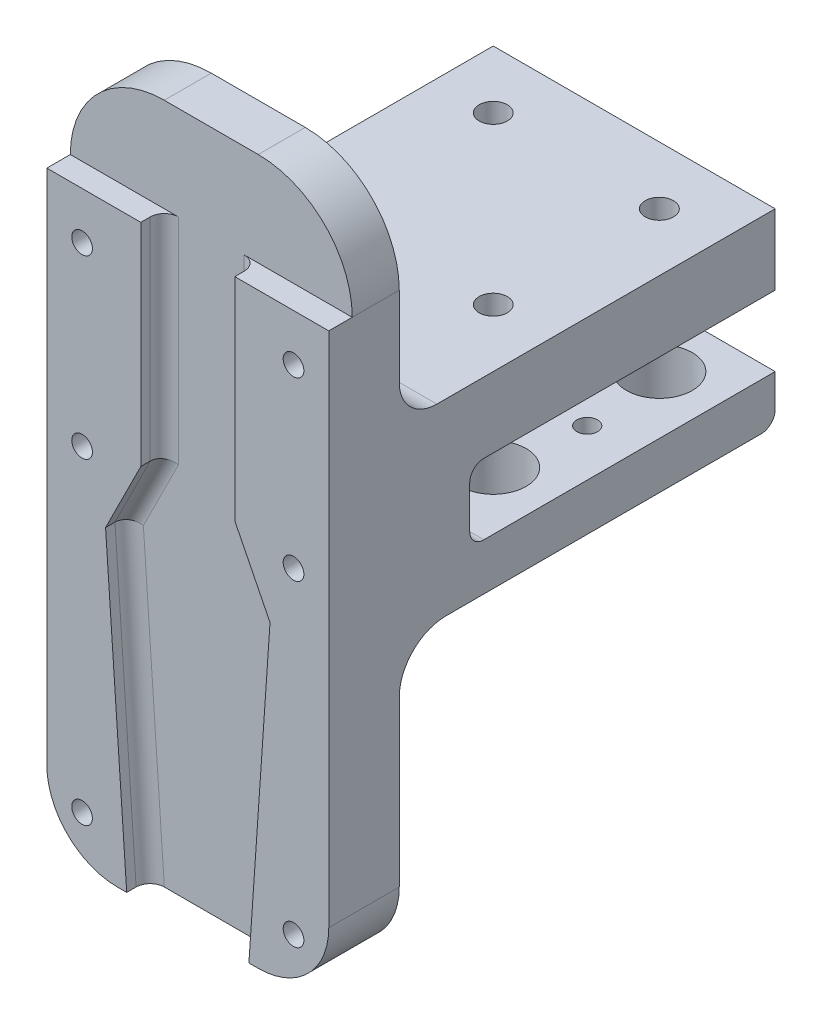
SolidWorks part; units mm, degrees
material "ABS"
ref_plane "Front Plane" through (0, 0, 0) normal (0, 0, 1) x (1, 0, 0)
ref_plane "Top Plane" through (0, 0, 0) normal (0, 1, 0) x (1, 0, 0)
ref_plane "Right Plane" through (0, 0, 0) normal (1, 0, 0) x (0, 0, -1)
sketch "草图8" plane through (0, 0, 0) normal (0, 1, 0) x (1, 0, 0)
  line L0 (-30, -30) -> (-17.6777, -17.6777)
  line L1 (-30, 30) -> (30, 30)
  line L2 (-30, 30) -> (-30, -30)
  line L3 (-30, -30) -> (30, -30)
  line L4 (30, 30) -> (30, -30)
  line L5 (-30, 30) -> (30, -30) construction
  line L6 (-30, -30) -> (30, 30) construction
  line L7 (-30, 30) -> (-17.6777, 17.6777)
  line L8 (17.6777, 17.6777) -> (30, 30)
  line L9 (17.6777, -17.6777) -> (30, -30)
  circle A0 centre (0, 0) radius 25
  circle A1 centre (17.6777, 17.6777) radius 3
  circle A2 centre (-17.6777, 17.6777) radius 3
  circle A3 centre (-17.6777, -17.6777) radius 3
  circle A4 centre (17.6777, -17.6777) radius 3
  point P0 (0, 0)
extrude "凸台-拉伸7" add sketch "草图8" along normal blind 15 contours A4 A0 A3 L0 L3 L9 | A4 L9 L4 L8 A1 A0 | A2 A0 A1 L8 L1 L7 | A3 A0 A2 L7 L2 L0 | A4 A0 A1 A2 A3
sketch "草图10" plane through (0, 0, 30) normal (0, 0, 1) x (1, 0, 0)
  line L1 (-30, 15) -> (30, 15)
  line L2 (-30, 15) -> (-30, 0)
  line L3 (-30, 0) -> (30, 0)
  line L4 (30, 15) -> (30, 0)
extrude "凸台-拉伸8" add sketch "草图10" along normal blind 30
sketch "草图11" plane through (0, 0, 0) normal (0, -1, 0) x (1, 0, 0)
  line L0 (-30, -30) -> (-30, 60) construction
  line L1 (30, 60) -> (-30, 60)
  line L2 (30, 60) -> (30, 50)
  line L3 (30, 50) -> (-30, 50)
  line L4 (-30, 60) -> (-30, 50)
extrude "凸台-拉伸9" add sketch "草图11" against normal blind 60
sketch "草图12" plane through (0, 0, 0) normal (0, -1, 0) x (-1, 0, 0)
  line L0 (-30, 30) -> (-30, -60) construction
  line L1 (30, -60) -> (-30, -60)
  line L2 (30, -60) -> (30, -50)
  line L3 (30, -50) -> (-30, -50)
  line L4 (-30, -60) -> (-30, -50)
extrude "凸台-拉伸10" add sketch "草图12" along normal blind 90
sketch "草图13" plane through (0, 0, 50) normal (0, 0, -1) x (-1, 0, 0)
  line L0 (30, -90) -> (30, 0) construction
  line L1 (-30, 0) -> (30, 0)
  line L2 (-30, 0) -> (-30, -15)
  line L3 (-30, -15) -> (30, -15)
  line L4 (30, 0) -> (30, -15)
  line L6 (-30, -15) -> (30, -15)
  line L7 (-30, -15) -> (-30, -25)
  line L8 (-30, -25) -> (30, -25)
  line L9 (30, -15) -> (30, -25)
  line M10 (-30, 0) -> (-30, -90)
  line M12 (30, -90) -> (30, 0)
extrude "凸台-拉伸11" add sketch "草图13" along normal up to surface (80 mm away) contours L8 L3 M10 M12 up to face at (0, 7.5, -30)
sketch "草图14" plane through (0, -25, 0) normal (0, -1, 0) x (1, 0, 0)
  line L0 (-30, -30) -> (-30, 50) construction
  line L1 (30, -30) -> (-30, -30)
  line L2 (30, -30) -> (30, 30)
  line L3 (30, 30) -> (-30, 30)
  line L4 (-30, -30) -> (-30, 30)
  line L5 (-30, 30) -> (-17.6777, 17.6777)
  line L6 (30, 30) -> (17.6777, 17.6777)
  line L7 (-17.6777, -17.6777) -> (-30, -30)
  line L8 (17.6777, -17.6777) -> (30, -30)
  circle A0 centre (0, 0) radius 25
  circle A1 centre (17.6777, 17.6777) radius 7
  circle A2 centre (17.6777, -17.6777) radius 7
  circle A3 centre (-17.6777, -17.6777) radius 7
  circle A4 centre (-17.6777, 17.6777) radius 7
extrude "切除-拉伸1" cut sketch "草图14" against normal up to surface (10 mm away) contours A0 A4 | A0 A1 | A0 A2 | A0 A3 | L5 A4 A0 | A0 A4 L5 | L6 A1 A0 | A0 A1 L6 | L8 A2 A0 | A0 A2 L8 | L7 A3 A0 | A0 A3 L7
sketch "草图15" plane through (0, 0, 0) normal (0, -1, 0) x (1, 0, 0)
  circle A0 centre (-17.6777, 17.6777) radius 6
  circle A1 centre (-17.6777, -17.6777) radius 6
  circle A2 centre (17.6777, -17.6777) radius 6
  circle A3 centre (17.6777, 17.6777) radius 6
extrude "切除-拉伸2" cut sketch "草图15" against normal blind 7
sketch "草图16" plane through (0, -25, 0) normal (0, -1, 0) x (-1, 0, 0)
  line L0 (30, 30) -> (30, -50) construction
  line L1 (-30, 30) -> (30, 30)
  line L2 (-30, 30) -> (-30, -30)
  line L3 (-30, -30) -> (30, -30)
  line L4 (30, 30) -> (30, -30)
  circle A0 centre (0, 0) radius 20
  circle A1 centre (-20, 0) radius 2.2
  circle A2 centre (0, 20) radius 2.2
  circle A3 centre (20, 0) radius 2.2
  circle A4 centre (0, -20) radius 2.2
extrude "切除-拉伸3" cut sketch "草图16" against normal up to surface (10 mm away) contours A0 A1 | A0 A1 | A0 A4 | A0 A4 | A0 A3 | A0 A3 | A0 A2 | A0 A2
sketch "草图17" plane through (0, -25, 0) normal (0, -1, 0) x (1, 0, 0)
  circle A0 centre (20, 0) radius 3.75
  circle A1 centre (0, -20) radius 3.75
  circle A2 centre (0, 20) radius 3.75
  circle A3 centre (-20, 0) radius 3.75
extrude "切除-拉伸4" cut sketch "草图17" against normal blind 4.5
sketch "草图18" plane through (0, 0, 50) normal (0, 0, -1) x (-1, 0, 0)
  line L0 (30, 0) -> (-30, 0) construction
  line L1 (-30, -15) -> (30, -15)
  line L2 (-30, -15) -> (-30, 0)
  line L3 (-30, 0) -> (30, 0)
  line L4 (30, -15) -> (30, 0)
extrude "凸台-拉伸12" add sketch "草图18" along normal blind 15
fillet "圆角1" radius 3 1 edges at (0, -25, -30)
fillet "圆角2" radius 10 1 edges at (0, -25, 50)
fillet "圆角3" radius 3 2 edges at (0, -15, 35) (0, 0, 35)
fillet "圆角4" radius 8 1 edges at (0, 15, 50)
sketch "草图19" plane through (0, 0, 60) normal (0, 0, 1) x (1, 0, 0)
  line L0 (0, 40) -> (0, -85)
  line L1 (-30, 60) -> (30, 60)
  line L5 (30, -90) -> (30, 60) construction
  line L10 (-30, 60) -> (30, 60)
  line L11 (-30, 60) -> (-30, 40)
  line L12 (-30, 40) -> (30, 40)
  line L13 (30, 60) -> (30, 40)
  line L14 (17.5, -20) -> (10, -5)
  line L15 (-30, 40) -> (30, 40)
  line L16 (-30, 40) -> (-30, -85)
  line L17 (-30, -85) -> (30, -85)
  line L18 (30, 40) -> (30, -85)
  line L19 (0, -85) -> (13, -85)
  line L20 (0, -85) -> (0, -20)
  line L21 (0, -20) -> (13, -20)
  line L22 (13, -85) -> (13, -20)
  line L23 (0, -85) -> (-13, -85)
  line L24 (0, -85) -> (0, -20)
  line L25 (0, -20) -> (-13, -20)
  line L26 (-13, -85) -> (-13, -20)
  line L27 (0, -85) -> (17.5, -85)
  line L28 (0, -85) -> (0, -20)
  line L29 (0, -20) -> (17.5, -20)
  line L30 (17.5, -85) -> (17.5, -20)
  line L31 (0, -85) -> (-17.5, -85)
  line L32 (0, -85) -> (0, -20)
  line L33 (0, -20) -> (-17.5, -20)
  line L34 (-17.5, -85) -> (-17.5, -20)
  line L35 (30, 40) -> (10, 40)
  line L36 (30, 40) -> (30, -5)
  line L37 (30, -5) -> (10, -5)
  line L38 (10, 40) -> (10, -5)
  line L39 (-30, 40) -> (-10, 40)
  line L40 (-30, 40) -> (-30, -5)
  line L41 (-30, -5) -> (-10, -5)
  line L42 (-10, 40) -> (-10, -5)
  line L43 (-10, -5) -> (-17.5, -20)
  line L44 (-17.5, -20) -> (-13, -85)
  line L45 (17.5, -20) -> (13, -85)
  line M40 (-30, 60) -> (-30, -90)
  line M42 (30, -90) -> (30, 60)
extrude "凸台-拉伸13" add sketch "草图19" along normal blind 5 contours L37 L14 L30 L17 M42 | L15 L38 L37 L18 | L42 L12 L41 M40 | L43 L41 L16 L17 L34 | L44 L34 L17 | L30 L45 L17
sketch "草图20" plane through (0, 0, 60) normal (0, 0, 1) x (1, 0, 0)
  line L1 (-30, -90) -> (30, -90)
  line L2 (-30, -90) -> (-30, -85)
  line L3 (-30, -85) -> (30, -85)
  line L4 (30, -90) -> (30, -85)
extrude "切除-拉伸5" cut sketch "草图20" against normal through all
fillet "圆角5" radius 3 6 edges at (10, 17.5, 60) (13.75, -12.5, 60) (15.25, -52.5, 60) (-15.25, -52.5, 60) (-13.75, -12.5, 60) (-10, 17.5, 60)
fillet "圆角6" radius 15 2 edges at (30, -85, 57.5) (-30, -85, 57.5)
sketch "草图22" plane through (0, 0, 65) normal (0, 0, 1) x (1, 0, 0)
  line L0 (30, 40) -> (30, -85)
  line L1 (0, -85) -> (30, -85)
  line L2 (9.9928, -85) -> (-9.9928, -85) construction
  line L3 (30, -85) -> (-30, 40)
  line L4 (30, -85) -> (-30, -85)
  line L5 (30, -85) -> (30, 40)
  line L6 (30, 40) -> (-30, 40)
  line L7 (-30, -85) -> (-30, 40)
  line L9 (22.5, 30) -> (-22.5, 30)
  line L10 (22.5, 30) -> (22.5, -75)
  line L11 (22.5, -75) -> (-22.5, -75)
  line L12 (-22.5, 30) -> (-22.5, -75)
  line L13 (22.5, 30) -> (-22.5, -75) construction
  line L14 (22.5, -75) -> (-22.5, 30) construction
  circle A0 centre (-22.5, 30) radius 2.2
  circle A1 centre (22.5, 30) radius 2.2
  circle A2 centre (-22.5, -75) radius 2.2
  circle A3 centre (22.5, -75) radius 2.2
  point P8 (0, -22.5)
extrude "切除-拉伸6" cut sketch "草图22" against normal through all contours L12 A2 L11 | L11 A2 L12 | L11 A3 L10 | L10 A3 L11 | L9 A0 L12 | L12 A0 L9 | L9 A1 L10 | L10 A1 L9
sketch "草图23" plane through (0, 0, 35) normal (0, 0, -1) x (-1, 0, 0)
  line L0 (30, -7.5) -> (-30, -7.5)
  line L1 (30, -3) -> (-30, -3)
  line L2 (30, -3) -> (30, -12)
  line L3 (30, -12) -> (-30, -12)
  line L4 (-30, -3) -> (-30, -12)
  circle A0 centre (0, -7.5) radius 22.5
  circle A1 centre (22.5, -7.5) radius 2.2
  circle A2 centre (-22.5, -7.5) radius 2.2
extrude "切除-拉伸7" cut sketch "草图23" against normal through all contours A0 A1 L0 | L0 A1 A0 | A0 A1 L0 | L0 A1 A0 | L0 A2 A0 | A0 A2 L0 | L0 A2 A0 | A0 A2 L0
sketch "草图24" plane through (0, 0, 50) normal (0, 0, -1) x (-1, 0, 0)
  line L1 (26.7, 30) -> (24.6, 33.6373)
  line L2 (24.6, 33.6373) -> (20.4, 33.6373)
  line L3 (20.4, 33.6373) -> (18.3, 30)
  line L4 (18.3, 30) -> (20.4, 26.3627)
  line L5 (20.4, 26.3627) -> (24.6, 26.3627)
  line L6 (24.6, 26.3627) -> (26.7, 30)
  line L7 (-26.7, 30) -> (-24.6, 26.3627)
  line L8 (-24.6, 26.3627) -> (-20.4, 26.3627)
  line L9 (-20.4, 26.3627) -> (-18.3, 30)
  line L10 (-18.3, 30) -> (-20.4, 33.6373)
  line L11 (-20.4, 33.6373) -> (-24.6, 33.6373)
  line L12 (-24.6, 33.6373) -> (-26.7, 30)
  line L13 (18.3, -7.5) -> (20.4, -11.1373)
  line L14 (20.4, -11.1373) -> (24.6, -11.1373)
  line L15 (24.6, -11.1373) -> (26.7, -7.5)
  line L16 (26.7, -7.5) -> (24.6, -3.8627)
  line L17 (24.6, -3.8627) -> (20.4, -3.8627)
  line L18 (20.4, -3.8627) -> (18.3, -7.5)
  line L19 (-26.7, -7.5) -> (-24.6, -11.1373)
  line L20 (-24.6, -11.1373) -> (-20.4, -11.1373)
  line L21 (-20.4, -11.1373) -> (-18.3, -7.5)
  line L22 (-18.3, -7.5) -> (-20.4, -3.8627)
  line L23 (-20.4, -3.8627) -> (-24.6, -3.8627)
  line L24 (-24.6, -3.8627) -> (-26.7, -7.5)
  line L25 (18.3, -75) -> (20.4, -78.6373)
  line L26 (20.4, -78.6373) -> (24.6, -78.6373)
  line L27 (24.6, -78.6373) -> (26.7, -75)
  line L28 (26.7, -75) -> (24.6, -71.3627)
  line L29 (24.6, -71.3627) -> (20.4, -71.3627)
  line L30 (20.4, -71.3627) -> (18.3, -75)
  line L31 (-18.3, -75) -> (-20.4, -71.3627)
  line L32 (-20.4, -71.3627) -> (-24.6, -71.3627)
  line L33 (-24.6, -71.3627) -> (-26.7, -75)
  line L34 (-26.7, -75) -> (-24.6, -78.6373)
  line L35 (-24.6, -78.6373) -> (-20.4, -78.6373)
  line L36 (-20.4, -78.6373) -> (-18.3, -75)
  circle A0 centre (22.5, 30) radius 4.2 construction
  circle A1 centre (-22.5, 30) radius 4.2 construction
  circle A2 centre (22.5, -7.5) radius 4.2 construction
  circle A3 centre (-22.5, -7.5) radius 4.2 construction
  circle A4 centre (22.5, -75) radius 4.2 construction
  circle A5 centre (-22.5, -75) radius 4.2 construction
extrude "切除-拉伸8" cut sketch "草图24" against normal blind 4.5
sketch "草图25" plane through (0, 0, 35) normal (0, 0, -1) x (-1, 0, 0)
  line L1 (18.3, -7.5) -> (20.4, -11.1373)
  line L2 (20.4, -11.1373) -> (24.6, -11.1373)
  line L3 (24.6, -11.1373) -> (26.7, -7.5)
  line L4 (26.7, -7.5) -> (24.6, -3.8627)
  line L5 (24.6, -3.8627) -> (20.4, -3.8627)
  line L6 (20.4, -3.8627) -> (18.3, -7.5)
  line L7 (-18.3, -7.5) -> (-20.4, -3.8627)
  line L8 (-20.4, -3.8627) -> (-24.6, -3.8627)
  line L9 (-24.6, -3.8627) -> (-26.7, -7.5)
  line L10 (-26.7, -7.5) -> (-24.6, -11.1373)
  line L11 (-24.6, -11.1373) -> (-20.4, -11.1373)
  line L12 (-20.4, -11.1373) -> (-18.3, -7.5)
  circle A0 centre (22.5, -7.5) radius 4.2 construction
  circle A1 centre (-22.5, -7.5) radius 4.2 construction
extrude "切除-拉伸9" cut sketch "草图25" against normal up to surface (15 mm away) up to face at (22.5, 30, 50)
sketch "草图26" plane through (0, 0, 35) normal (0, 0, -1) x (-1, 0, 0)
  circle A0 centre (22.5, -7.5) radius 4.2
  circle A1 centre (-22.5, -7.5) radius 4.2
extrude "切除-拉伸10" cut sketch "草图26" against normal up to surface (15 mm away) up to face at (-22.5, -75, 50)
fillet "圆角7" radius 20 2 edges at (-30, 60, 55) (30, 60, 55)
sketch "草图27" plane through (0, 15, 0) normal (0, 1, 0) x (1, 0, 0)
  line L0 (0, 0) -> (30, 0)
  line L1 (30, 30) -> (30, -42) construction
  line L2 (0, 0) -> (0, 30)
  line L3 (-30, 30) -> (30, 30) construction
